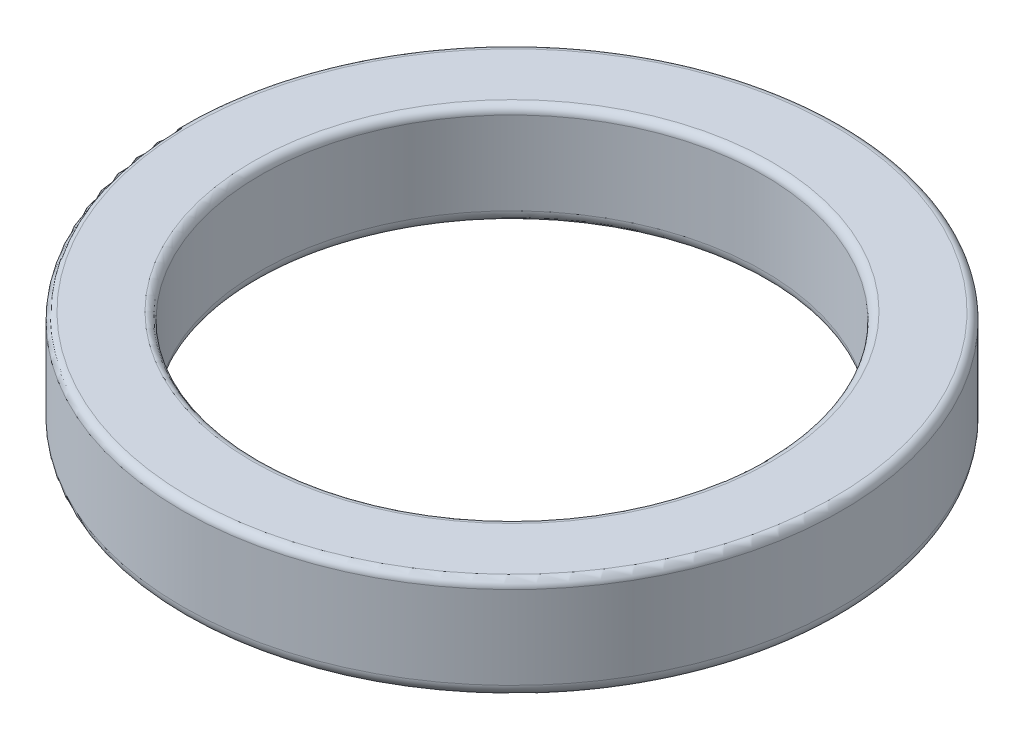
SolidWorks part; units mm, degrees
ref_plane "Front Plane" through (0, 0, 0) normal (0, 0, 1) x (1, 0, 0)
ref_plane "Top Plane" through (0, 0, 0) normal (0, 1, 0) x (1, 0, 0)
ref_plane "Right Plane" through (0, 0, 0) normal (1, 0, 0) x (0, 0, -1)
sketch "Sketch1" plane through (0, 0, 0) normal (0, 1, 0) x (1, 0, 0)
  circle A0 centre (0, 0) radius 9.7085
  circle A1 centre (0, 0) radius 12.7084
  dimension "D1" = 19.4169
  dimension "D2" = 3
extrude "Boss-Extrude1" add sketch "Sketch1" along normal blind 4
fillet "Fillet1" radius 0.3 1 edges at (0, 4, 12.7084)
fillet "Fillet5" radius 0.3 1 edges at (0, 4, 9.7085)
fillet "Fillet6" radius 0.5 1 edges at (0, 0, 12.7084)
fillet "Fillet7" radius 0.5 1 edges at (0, 0, 9.7085)
